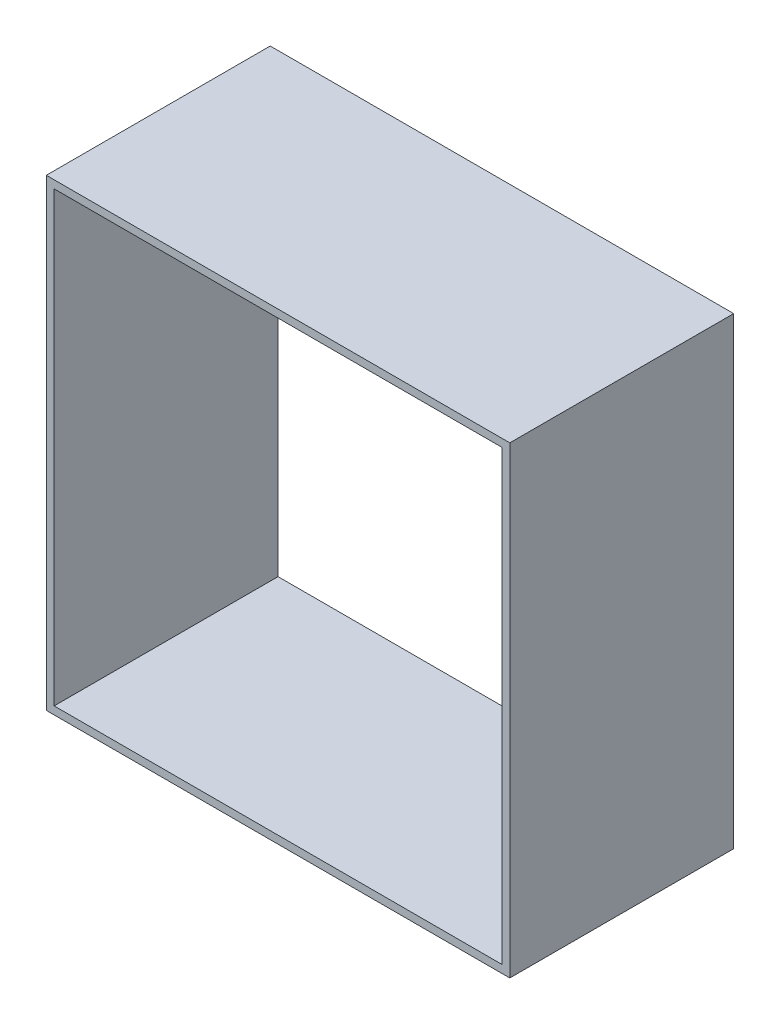
SolidWorks part; units mm, degrees
ref_plane "Front Plane" through (0, 0, 0) normal (0, 0, 1) x (1, 0, 0)
ref_plane "Top Plane" through (0, 0, 0) normal (0, 1, 0) x (1, 0, 0)
ref_plane "Right Plane" through (0, 0, 0) normal (1, 0, 0) x (0, 0, -1)
sketch "Sketch1" plane through (0, 0, 0) normal (0, 0, 1) x (1, 0, 0)
  line L1 (-10, 10) -> (10, 10)
  line L2 (-10, 10) -> (-10, -10)
  line L3 (-10, -10) -> (10, -10)
  line L4 (10, 10) -> (10, -10)
  line L5 (-10, 10) -> (10, -10) construction
  line L6 (-10, -10) -> (10, 10) construction
  line L7 (-10.35, 10.35) -> (10.35, 10.35)
  line L8 (-10.35, 10.35) -> (-10.35, -10.35)
  line L9 (-10.35, -10.35) -> (10.35, -10.35)
  line L10 (10.35, 10.35) -> (10.35, -10.35)
  line L11 (-10.35, 10.35) -> (10.35, -10.35) construction
  line L12 (-10.35, -10.35) -> (10.35, 10.35) construction
  point P0 (0, 0)
  point P6 (0, 0)
  dimension "D1" = 0.35
  dimension "D2" = 0.35
  dimension "D3" = 20
  dimension "D4" = 20
extrude "Boss-Extrude1" add sketch "Sketch1" along normal blind 10
